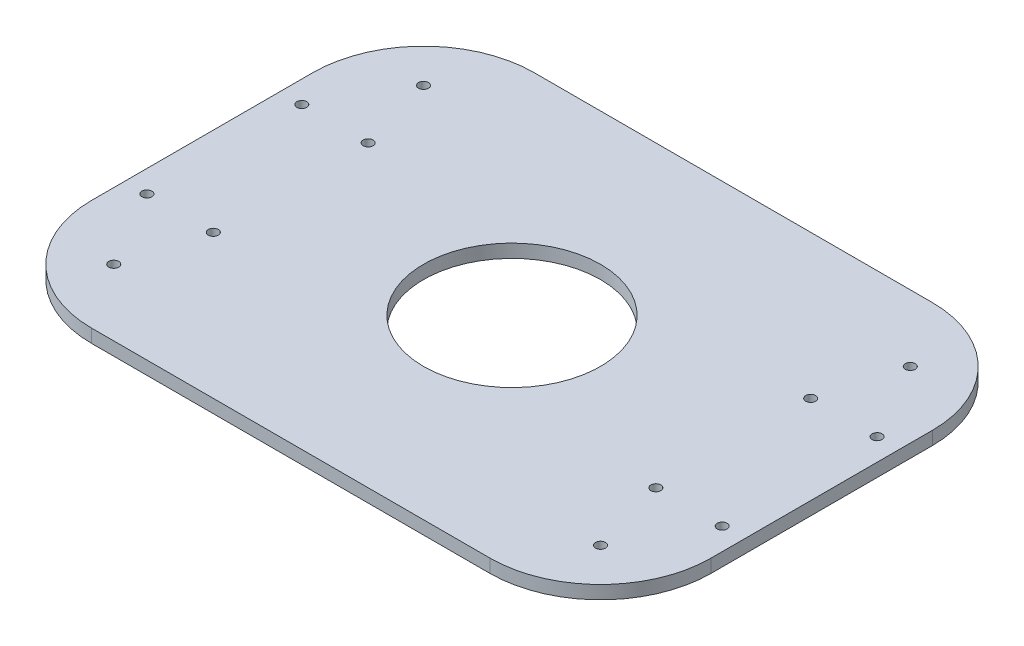
SolidWorks part; units mm, degrees
ref_plane "前视基准面" through (0, 0, 0) normal (0, 0, 1) x (1, 0, 0)
ref_plane "上视基准面" through (0, 0, 0) normal (0, 1, 0) x (1, 0, 0)
ref_plane "右视基准面" through (0, 0, 0) normal (1, 0, 0) x (0, 0, -1)
other "Configuration Table"
sketch "草图6" plane through (0, 0, 0) normal (0, 1, 0) x (1, 0, 0)
  line L0 (0, 0) -> (0, 244.2569) construction
  line L1 (0, 0) -> (293.6379, 0) construction
  line L3 (-220, 100) -> (220, 100)
  line L4 (-220, 100) -> (-220, -100)
  line L5 (-220, -100) -> (220, -100)
  line L6 (220, 100) -> (220, -100)
  circle A0 centre (0, 0) radius 85 construction
  circle A1 centre (0, 0) radius 40
  dimension "D1" = 170
  dimension "D4" = 80
  dimension "D2" = 200
  dimension "D3" = 440
extrude "凸台-拉伸2" add sketch "草图6" along normal blind 6
sketch "草图7" plane through (0, 6, 0) normal (0, 1, 0) x (1, 0, 0)
  line L0 (0, 0) -> (281.8886, 0) construction
  line L1 (-90, 100) -> (90, 100) construction
  line L2 (-140, 50) -> (-140, -50)
  line L3 (-90, -100) -> (90, -100) construction
  line L4 (140, 50) -> (140, -50)
  line L5 (0, 0) -> (0, 132.2554) construction
  line L10 (-220, 100) -> (-220, -100)
  line L11 (-220, -100) -> (220, -100)
  line L12 (220, -100) -> (220, 100)
  line L13 (220, 100) -> (-220, 100)
  line L14 (-220, 100) -> (-220, -100)
  line L15 (-220, -100) -> (220, -100)
  line L16 (220, -100) -> (220, 100)
  line L17 (220, 100) -> (-220, 100)
  arc A0 (-90, -100) -> (-140, -50) centre (-90, -50) cw
  arc A1 (90, -100) -> (140, -50) centre (90, -50) ccw
  arc A2 (140, 50) -> (90, 100) centre (90, 50) ccw
  arc A3 (-90, 100) -> (-140, 50) centre (-90, 50) ccw
  circle A4 centre (100, 35) radius 2.25
  circle A5 centre (130, 35) radius 2.25
  circle A6 centre (110, 70) radius 2.25
  circle A7 centre (-110, 70) radius 2.25
  circle A8 centre (-130, 35) radius 2.25
  circle A9 centre (-100, 35) radius 2.25
  circle A10 centre (-100, -35) radius 2.25
  circle A11 centre (-130, -35) radius 2.25
  circle A12 centre (-110, -70) radius 2.25
  circle A13 centre (110, -70) radius 2.25
  circle A14 centre (130, -35) radius 2.25
  circle A15 centre (100, -35) radius 2.25
  point P10 (-140, -100)
  point P13 (140, -100)
  point P16 (140, 100)
  point P25 (0, 0)
  point P46 (0, 0)
  line M14 (-220, 100) -> (-220, -100)
  line M15 (-220, -100) -> (220, -100)
  line M16 (220, -100) -> (220, 100)
  line M17 (220, 100) -> (-220, 100)
  dimension "D3" = 50
  dimension "D4" = 4.5
  dimension "D1" = 200
  dimension "D2" = 280
  dimension "D5" = 35
  dimension "D6" = 30
  dimension "D7" = 100
  dimension "D8" = 110
  dimension "D9" = 70
  dimension "D10" = 0
extrude "切除-拉伸1" cut sketch "草图7" against normal blind 10 contours A3 A0 L2 M17 M14 M15 | A2 L4 A1 M15 M16 M17 | A8 | A9 | A7 | A6 | A4 | A5 | A14 | A15 | A13 | A12 | A10 | A11
